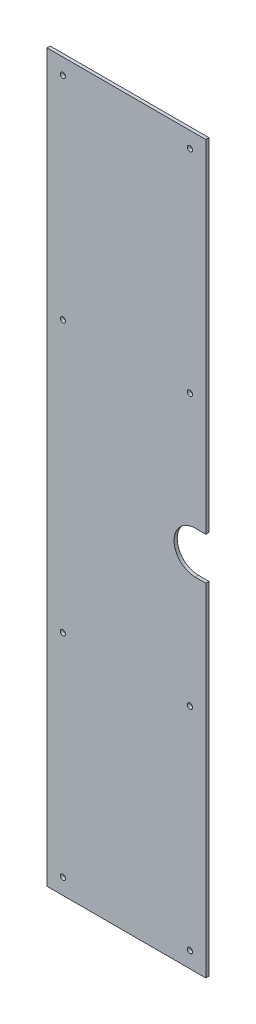
SolidWorks part; units mm, degrees
ref_plane "Front Plane" through (0, 0, 0) normal (1, 0, 0) x (0, 1, 0)
ref_plane "Top Plane" through (0, 0, 0) normal (0, 0, 1) x (0, 1, 0)
ref_plane "Right Plane" through (0, 0, 0) normal (0, 1, 0) x (-1, 0, 0)
sketch "Sketch1" plane through (0, 0, 0) normal (0, 0, 1) x (0, 1, 0)
  line L0 (0, 0) -> (0, -75) construction
  line L1 (-343, -75) -> (343, -75)
  line L2 (-343, -75) -> (-343, 75)
  line L3 (-343, 75) -> (343, 75)
  line L4 (343, -75) -> (343, 75)
  line L5 (-343, -75) -> (343, 75) construction
  line L6 (-343, 75) -> (343, -75) construction
  line L7 (-343, 0) -> (343, 0) construction
  line L8 (-313, 75) -> (-313, -75) construction
  line L9 (-343, 45) -> (343, 45) construction
  line L10 (0, 75) -> (0, -75) construction
  line L11 (-343, -45) -> (343, -45) construction
  line L12 (-313, 15) -> (-313, -45)
  line L13 (-313, -45) -> (-253, -45)
  line L14 (313, 15) -> (313, -45)
  line L15 (313, -45) -> (253, -45)
  arc A0 (-253, -45) -> (-313, 15) centre (-313, -45) ccw
  circle A1 centre (-128, -60) radius 2.5
  circle A2 centre (-328, 60) radius 2.5
  circle A6 centre (-328, -60) radius 2.5
  circle A8 centre (-128, 60) radius 2.5
  circle A10 centre (328, -60) radius 2.5
  circle A11 centre (328, 60) radius 2.5
  circle A12 centre (128, -60) radius 2.5
  circle A13 centre (128, 60) radius 2.5
  arc A14 (253, -45) -> (313, 15) centre (313, -45) cw
  circle A19 centre (328, 0) radius 2.5
  circle A20 centre (-328, 0) radius 2.5
  circle A21 centre (-328, -140) radius 2.5
  circle A22 centre (-328, 140) radius 2.5
  circle A23 centre (328, 140) radius 2.5
  circle A24 centre (328, -140) radius 2.5
  point P0 (0, 0)
  point P10 (-313, -45)
  dimension "D3" = 60
  dimension "D7" = 5
  dimension "D12" = 200
  dimension "D1" = 686
  dimension "D2" = 150
  dimension "D4" = 30
  dimension "D5" = 30
  dimension "D6" = 15
  dimension "D8" = 15
  dimension "D9" = 2
  dimension "D10" = 200
  dimension "D11" = 15
extrude "Boss-Extrude1" add sketch "Sketch1" along normal blind 3
sketch "Sketch2" [suppressed] plane through (0, 0, 3) normal (0, 0, 1) x (1, 0, 0)
  line L0 (75, 335) -> (-75, 335) construction
  line L1 (-45, 285) -> (-25, 285)
  line L2 (-45, 285) -> (-45, 260)
  line L3 (-45, 260) -> (-25, 260)
  line L4 (-25, 285) -> (-25, 260)
  line L5 (-45, 285) -> (-25, 260) construction
  line L6 (-45, 260) -> (-25, 285) construction
  line L7 (75, -335) -> (75, 335) construction
  point P0 (-35, 272.5)
  dimension "D1" = 25
  dimension "D2" = 20
  dimension "D3" = 50
  dimension "D4" = 100
extrude "Cut-Extrude2" [suppressed] cut sketch "Sketch2" against normal blind 3
sketch "Sketch3" [suppressed] plane through (0, 0, 3) normal (0, 0, 1) x (1, 0, 0)
  line L0 (-285, 343) -> (-285, 293)
  line L1 (335, 343) -> (-335, 343) construction
  line L2 (-285, 293) -> (-335, 293)
  line L3 (-335, -343) -> (-335, 343) construction
  line L4 (0, 0) -> (0, -343) construction
  line L5 (335, -343) -> (-335, -343) construction
  line L6 (285, 343) -> (285, 293)
  line L7 (285, 293) -> (335, 293)
  line L8 (1.65, 0) -> (-1.65, 0) construction
  line L9 (285, -293) -> (335, -293)
  line L10 (285, -343) -> (285, -293)
  line L11 (-285, -343) -> (-285, -293)
  line L12 (-285, -293) -> (-335, -293)
  circle A0 centre (-320, 243) radius 2.5
  circle A1 centre (-235, 328) radius 2.5
  circle A3 centre (235, 328) radius 2.5
  circle A4 centre (320, 243) radius 2.5
  circle A5 centre (320, -243) radius 2.5
  circle A6 centre (235, -328) radius 2.5
  circle A7 centre (-235, -328) radius 2.5
  circle A8 centre (-320, -243) radius 2.5
  circle M9 centre (-320, 328) radius 2.5
  line M10 (335, -343) -> (335, 343)
  line M11 (335, 343) -> (-335, 343)
  line M12 (-335, 343) -> (-335, -343)
  line M13 (-335, -343) -> (335, -343)
  circle M15 centre (-320, -328) radius 2.5
  circle M16 centre (320, -328) radius 2.5
  circle M18 centre (320, 328) radius 2.5
  dimension "D4" = 5
  dimension "D5" = 5
  dimension "D1" = 50
  dimension "D2" = 50
  dimension "D3" = 50
  dimension "D6" = 50
  dimension "D7" = 15
  dimension "D8" = 15
extrude "Cut-Extrude3" [suppressed] cut sketch "Sketch3" against normal blind 10 contours L11 L12 M12 M13 M15 | L2 L0 M11 M12 M9 | L6 L7 M10 M11 M18 | L10 L9 M13 M10 M16 | A7 | A8 | A0 | A1 | A3 | A4 | A5 | A6
sketch "Sketch4" plane through (0, 0, 3) normal (0, 0, 1) x (1, 0, 0)
  line L1 (75, 20) -> (65, 20)
  line L2 (75, -343) -> (75, 343) construction
  line L3 (65, -20) -> (75, -20)
  line L4 (75, -20) -> (75, 20)
  arc A0 (65, 20) -> (65, -20) centre (65, 0) ccw
  point P6 (0, 0)
  line M4 (75, -343) -> (75, 343)
  dimension "D1" = 10
  dimension "D2" = 20
extrude "Cut-Extrude4" cut sketch "Sketch4" against normal blind 10 and the other way through all contours L1 A0 L3 M4
